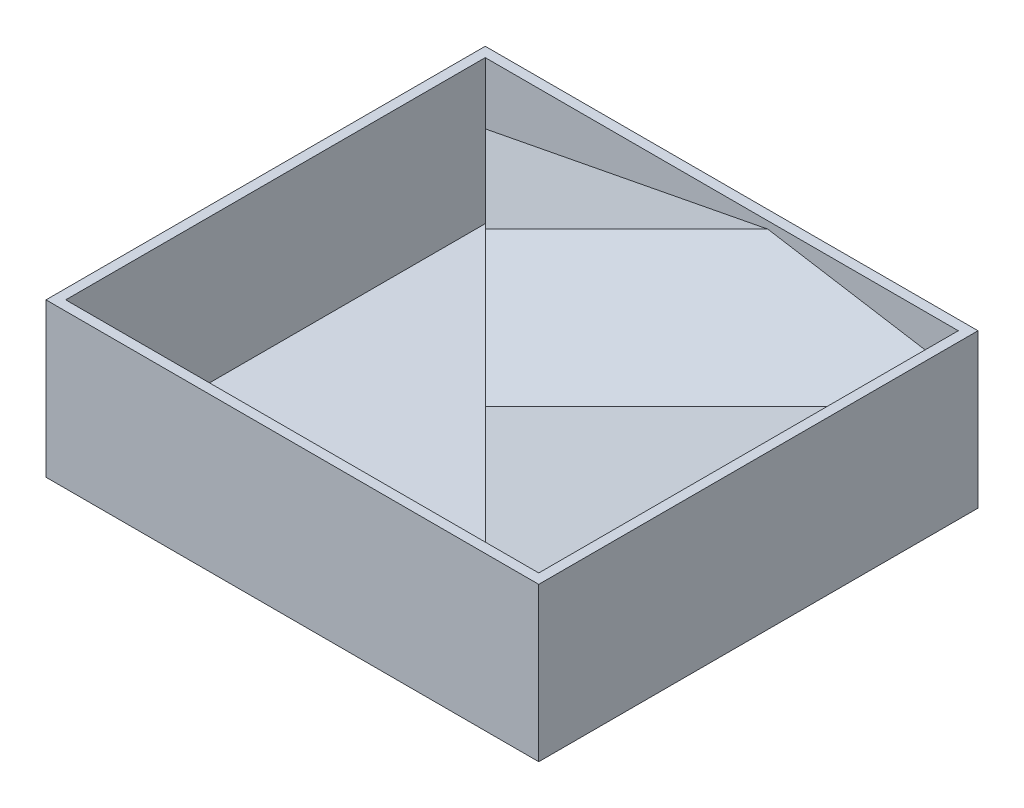
SolidWorks part; units mm, degrees
ref_plane "Front Plane" through (0, 0, 0) normal (0, 0, 1) x (1, 0, 0)
ref_plane "Top Plane" through (0, 0, 0) normal (0, 1, 0) x (1, 0, 0)
ref_plane "Right Plane" through (0, 0, 0) normal (1, 0, 0) x (0, 0, -1)
other "Configuration Table"
sketch "Sketch1" plane through (0, 0, 0) normal (0, 1, 0) x (1, 0, 0)
  line L1 (-62.4779, 63.937) -> (64.6003, 63.937)
  line L2 (-62.4779, 63.937) -> (-62.4779, -49.3456)
  line L3 (-62.4779, -49.3456) -> (64.6003, -49.3456)
  line L4 (64.6003, 63.937) -> (64.6003, -49.3456)
extrude "Boss-Extrude1" add sketch "Sketch1" along normal blind 39.624
shell "抽壳1" thickness 2.54
ref_plane "基准面1" through (0.7296, 0, -0.7296) normal (-0.7071, 0, 0.7071) x (0.7071, 0, 0.7071)
sketch "草图1" plane through (0.7296, 0, -0.7296) normal (-0.7071, 0, 0.7071) x (0.7071, 0, 0.7071)
  line L0 (-85.797, 21.082) -> (-34.23, 35.134)
  line L1 (-34.23, 35.134) -> (7.726, 25.357)
  line L2 (7.726, 25.357) -> (111.514, 39.624)
rib "official_rib_block20" sketch "草图1" sketch "草图1" thickness 2.54 parameters "D1"=2.54
